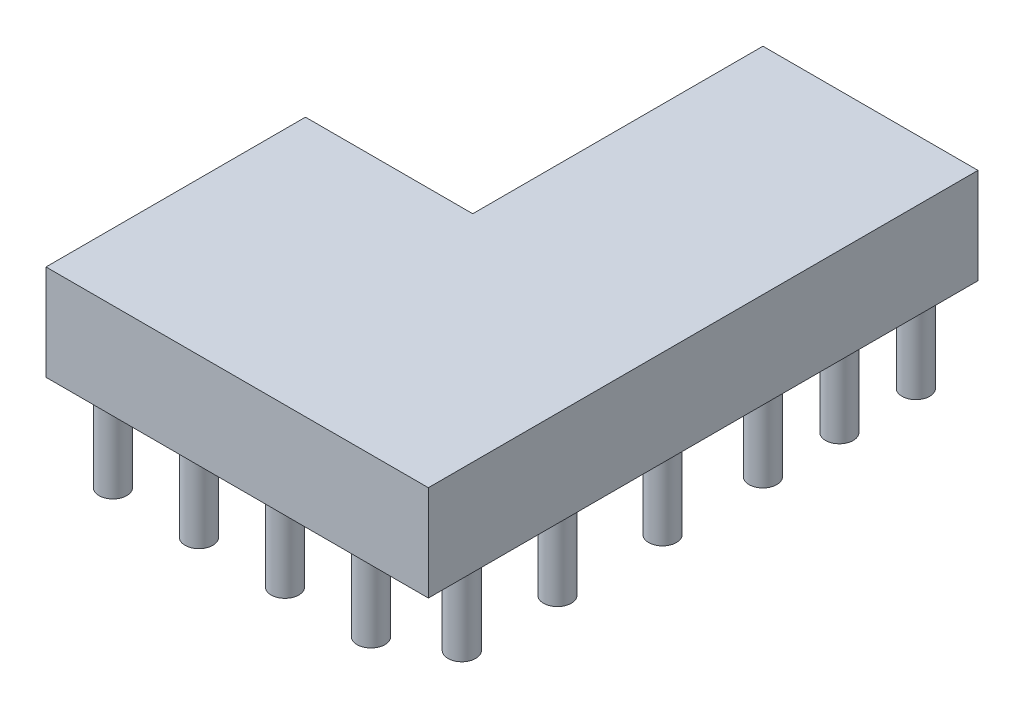
SolidWorks part; units mm, degrees
ref_plane "Спереди" through (0, 0, 0) normal (0, 0, 1) x (1, 0, 0)
ref_plane "Сверху" through (0, 0, 0) normal (0, 1, 0) x (1, 0, 0)
ref_plane "Справа" through (0, 0, 0) normal (1, 0, 0) x (0, 0, -1)
sketch "Эскиз2" plane through (0, 0, 0) normal (0, 1, 0) x (1, 0, 0)
  line L0 (-34.7863, -46.9714) -> (30.2137, -46.9714)
  line L1 (-34.7863, -46.9714) -> (-34.7863, -12.6857)
  line L2 (-34.7863, -12.6857) -> (5.2137, -12.6857)
  line L3 (30.2137, -46.9714) -> (30.2137, -6.9714)
  line L4 (-34.7863, -46.9714) -> (30.2137, -6.9714) construction
  line L5 (-34.7863, -12.6857) -> (30.2137, -46.9714) construction
  line L6 (30.2137, -6.9714) -> (30.2137, 53.0286)
  line L7 (30.2137, 53.0286) -> (5.2137, 53.0286)
  line L8 (5.2137, -12.6857) -> (5.2137, 53.0286)
  line L9 (-30.7783, -2.6857) -> (-4.7863, -2.6857)
  line L10 (-4.7863, -2.6857) -> (-4.7863, 58.0286)
  line L11 (-4.7863, 58.0286) -> (40.2137, 58.0286)
  line L12 (40.2137, 58.0286) -> (40.2137, -56.9714)
  line L13 (40.2137, -56.9714) -> (-39.7863, -56.9714)
  line L14 (-39.7863, -56.9714) -> (-39.7863, -2.6857)
  line L15 (-39.7863, -2.6857) -> (-30.7783, -2.6857)
  point P0 (-4.7863, -28.5098)
  dimension "D1" = 40
  dimension "D2" = 65
  dimension "D3" = 60
  dimension "D4" = 25
  dimension "D5" = 10
  dimension "D6" = 5
  dimension "D7" = 10
  dimension "D8" = 10
  dimension "D9" = 5
  dimension "D10" = 10
extrude "Бобышка-Вытянуть1" add sketch "Эскиз2" against normal blind 20
sketch "Эскиз3" plane through (0, 0, 0) normal (0, 1, 0) x (1, 0, 0)
  line L0 (5.2137, 53.0286) -> (30.2137, 53.0286)
  line L1 (30.2137, 53.0286) -> (30.2137, -46.9714)
  line L2 (30.2137, -46.9714) -> (-34.7863, -46.9714)
  line L3 (-34.7863, -46.9714) -> (-34.7863, -12.6857)
  line L4 (-34.7863, -12.6857) -> (5.2137, -12.6857)
  line L5 (5.2137, 53.0286) -> (5.2137, -12.6857) construction
  line L6 (5.2137, -12.6857) -> (-34.7863, -12.6857) construction
  line L7 (5.2137, -12.6857) -> (5.2137, 53.0286)
extrude "Бобышка-Вытянуть2" add sketch "Эскиз3" against normal blind 9
sketch "Эскиз4" plane through (0, -20, 0) normal (0, -1, 0) x (1, 0, 0)
  line L0 (-34.7863, 46.9714) -> (40.2137, 46.9714) construction
  line L1 (40.2137, 56.9714) -> (40.2137, -58.0286) construction
  line L2 (30.2137, -51.7218) -> (30.2137, 56.9714) construction
  line L3 (30.2137, 46.9714) -> (30.2137, -53.0286) construction
  line L4 (-39.7863, 56.9714) -> (40.2137, 56.9714) construction
  line L5 (30.2137, 46.9714) -> (-39.7863, 46.9714) construction
  line L6 (-39.7863, 2.6857) -> (-39.7863, 56.9714) construction
  line L7 (-39.7863, 46.9714) -> (-39.7863, 56.9714) construction
  line L8 (-39.7863, 56.9714) -> (40.2137, 56.9714) construction
  line L9 (40.2137, 56.9714) -> (40.2137, 46.9714) construction
  line L10 (40.2137, 51.9714) -> (-39.7863, 51.9714) construction
  line L11 (30.2137, -51.7218) -> (30.2137, -58.0286) construction
  line L12 (40.2137, -58.0286) -> (-4.7863, -58.0286) construction
  line L13 (30.2137, -58.0286) -> (40.2137, -58.0286) construction
  line L14 (40.2137, -58.0286) -> (40.2137, 56.9714) construction
  line L15 (40.2137, 56.9714) -> (30.2137, 56.9714) construction
  line L16 (30.2137, 56.9714) -> (40.2137, 56.9714) construction
  line L17 (35.2137, -58.0286) -> (35.2137, 56.9714) construction
  line L18 (5.2137, 12.6857) -> (-39.7863, 12.6857) construction
  line L19 (-39.7863, 12.6857) -> (-39.7863, 2.6857) construction
  line L20 (-39.7863, 2.6857) -> (5.2137, 2.6857) construction
  line L21 (5.2137, -53.0286) -> (5.2137, 12.6857) construction
  line L22 (5.2137, 2.6857) -> (5.2137, 12.6857) construction
  line L23 (-39.7863, 7.6857) -> (5.2137, 7.6857) construction
  line L24 (-4.7863, -58.0286) -> (-4.7863, 12.6857) construction
  line L25 (-4.7863, 12.6857) -> (5.2137, 12.6857) construction
  line L26 (5.2137, 12.6857) -> (5.2137, -58.0286) construction
  line L27 (5.2137, -58.0286) -> (-4.7863, -58.0286) construction
  line L28 (-4.7863, -58.0286) -> (0.2137, -58.0286) construction
  line L29 (0.2137, -58.0286) -> (0.2137, 12.6857) construction
  circle A1 centre (35.2137, 24.9714) radius 2.9
  circle A2 centre (35.2137, 2.9714) radius 2.9
  circle A3 centre (35.2137, -18.0286) radius 2.9
  circle A4 centre (35.2137, -34.0286) radius 2.9
  circle A5 centre (35.2137, -50.0286) radius 2.9
  circle A6 centre (23.2137, 51.9714) radius 2.9
  circle A7 centre (5.2137, 51.9714) radius 2.9
  circle A8 centre (-12.7863, 51.9714) radius 2.9
  circle A9 centre (-30.7863, 51.9714) radius 2.9
  circle A10 centre (-28.7863, 7.6857) radius 2.9
  circle A11 centre (-12.7863, 7.6857) radius 2.9
  circle A13 centre (0.2137, -52.3143) radius 2.9
  circle A14 centre (0.2137, -34.3143) radius 2.9
  circle A15 centre (0.2137, -16.3143) radius 2.9
  circle A16 centre (35.2137, 44.9714) radius 2.9
  circle A17 centre (0.2137, 7.6857) radius 2.9
  dimension "D1" = 17
  dimension "D2" = 18
  dimension "D3" = 18
  dimension "D4" = 18
  dimension "D6" = 20
  dimension "D5" = 12
  dimension "D7" = 22
  dimension "D8" = 21
  dimension "D9" = 16
  dimension "D10" = 5.8
  dimension "D11" = 16
  dimension "D12" = 5
  dimension "D13" = 13
  dimension "D14" = 16
  dimension "D15" = 24
  dimension "D16" = 18
  dimension "D17" = 18
  dimension "D18" = 5.8
  dimension "D19" = 5.8
  dimension "D20" = 5.8
  dimension "D21" = 5.8
  dimension "D22" = 5.8
  dimension "D23" = 5.8
  dimension "D24" = 5.8
  dimension "D25" = 5.8
  dimension "D26" = 5.8
  dimension "D27" = 5.8
  dimension "D28" = 5.8
  dimension "D29" = 5.8
  dimension "D30" = 5.8
  dimension "D31" = 5.8
  dimension "D32" = 5.8
extrude "Бобышка-Вытянуть3" add sketch "Эскиз4" along normal blind 18
